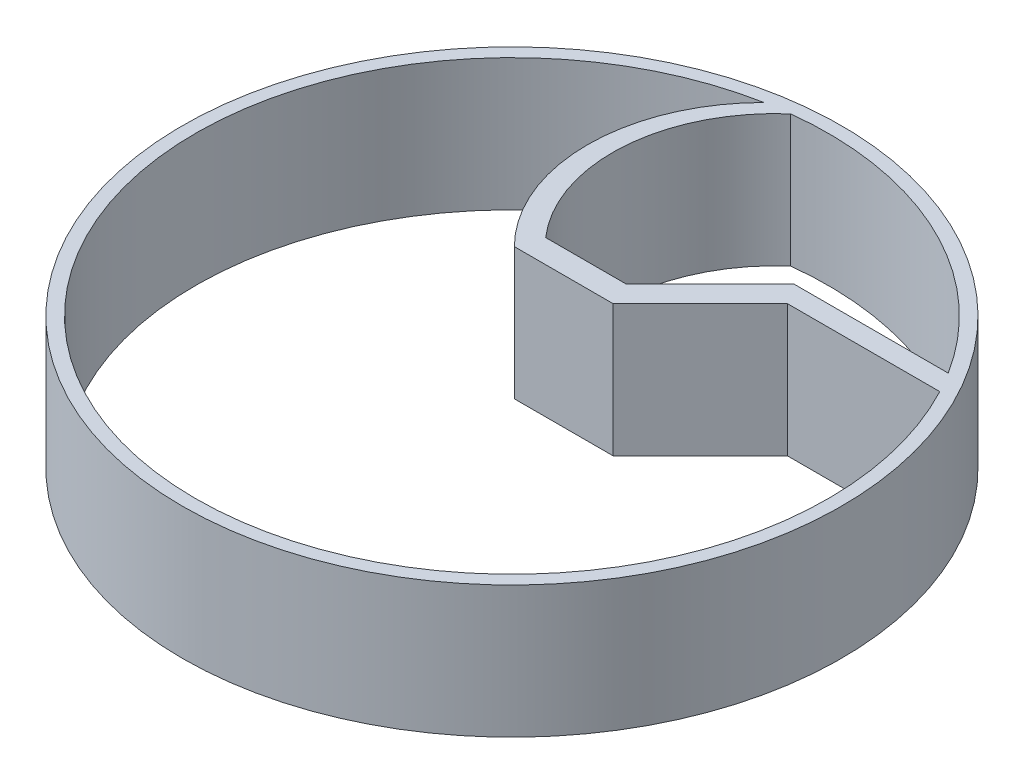
SolidWorks part; units mm, degrees
ref_plane "Front Plane" through (0, 0, 0) normal (0, 0, 1) x (1, 0, 0)
ref_plane "Top Plane" through (0, 0, 0) normal (0, 1, 0) x (1, 0, 0)
ref_plane "Right Plane" through (0, 0, 0) normal (1, 0, 0) x (0, 0, -1)
sketch "Sketch1" plane through (0, 0, 0) normal (0, 1, 0) x (1, 0, 0)
  circle A0 centre (0, 0) radius 2.5
  circle A1 centre (0, 0) radius 2.4
  dimension "D1" = 5
  dimension "D2" = 4.8
extrude "Boss-Extrude1" add sketch "Sketch1" along normal blind 1
sketch "Sketch2" plane through (0, 0, 0) normal (0, 1, 0) x (1, 0, 0)
  line L0 (2.1196, 1.1257) -> (0.9642, 1.1257)
  line L1 (0.9642, 1.1257) -> (0.3029, 0.4644)
  line L2 (0.3029, 0.4644) -> (-0.446, 0.4644)
  line L3 (2.0307, 1.2791) -> (0.8592, 1.2791)
  line L4 (0.8592, 1.2791) -> (0.2229, 0.6428)
  line L5 (0.2229, 0.6428) -> (-0.387, 0.6428)
  circle A0 centre (0, 0) radius 2.4 construction
  arc A1 (-0.446, 0.4644) -> (-0.446, 2.3582) centre (0.5009, 1.4113) cw
  arc A2 (-0.387, 0.6428) -> (-0.2701, 2.3848) centre (0.5424, 1.4554) cw
  arc A3 (-0.446, 2.3582) -> (-0.2701, 2.3848) centre (0, 0) cw
  arc A4 (2.0307, 1.2791) -> (2.1196, 1.1257) centre (0, 0) cw
extrude "Boss-Extrude2" add sketch "Sketch2" along normal blind 1
